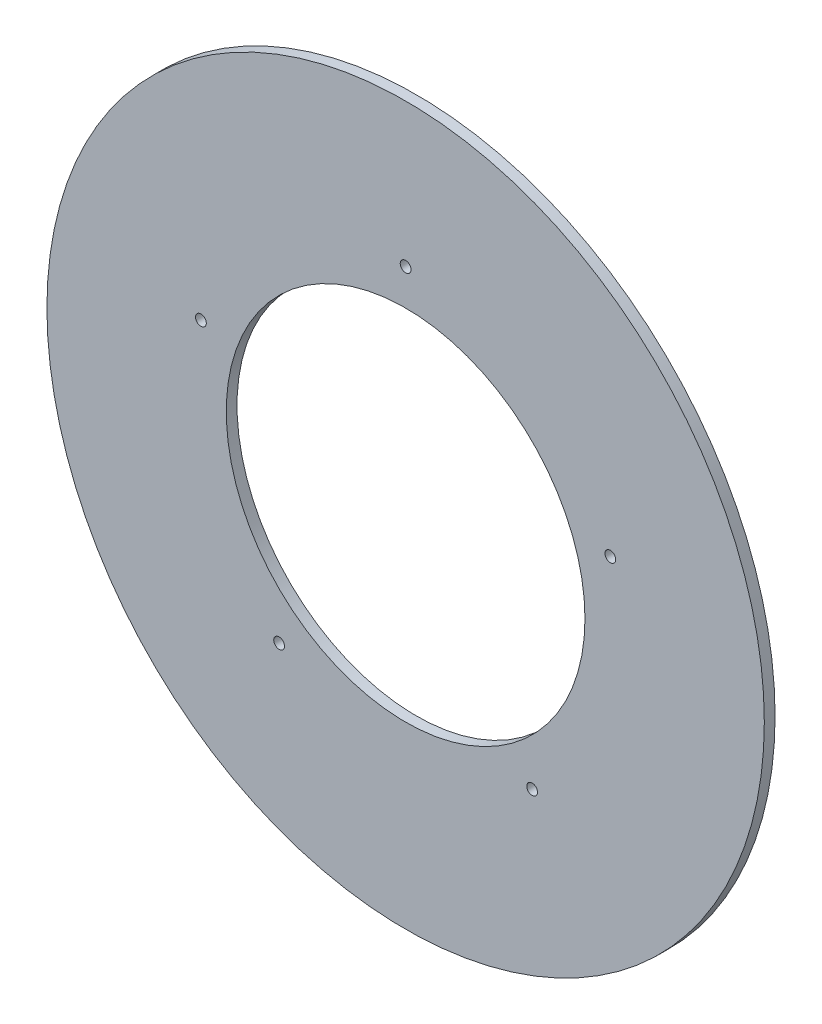
SolidWorks part; units mm, degrees
other "Markup1"
sketch "Sketch5" plane through (-50, -50, 1.5) normal (0, 0, 1) x (1, 0, 0)
ref_plane "Front Plane" through (0, 0, 0) normal (0, 0, 1) x (1, 0, 0)
ref_plane "Top Plane" through (0, 0, 0) normal (0, 1, 0) x (1, 0, 0)
ref_plane "Right Plane" through (0, 0, 0) normal (1, 0, 0) x (0, 0, -1)
sketch "Sketch1" plane through (0, 0, 0) normal (0, 0, 1) x (1, 0, 0)
  circle A0 centre (0, 0) radius 50
  circle A1 centre (0, 0) radius 25
  dimension "D1" = 100
  dimension "D2" = 50
extrude "Boss-Extrude1" add sketch "Sketch1" along normal blind 1.5
sketch "Sketch2" plane through (0, 0, 1.5) normal (0, 0, 1) x (1, 0, 0)
  line L5 (0, 30) -> (-28.5317, 9.2705) construction
  line L6 (-28.5317, 9.2705) -> (-17.6336, -24.2705) construction
  line L7 (-17.6336, -24.2705) -> (17.6336, -24.2705) construction
  line L8 (17.6336, -24.2705) -> (28.5317, 9.2705) construction
  line L9 (28.5317, 9.2705) -> (0, 30) construction
  circle A1 centre (0, 0) radius 50 construction
  circle A7 centre (0, 30) radius 0.75
  circle A17 centre (28.5317, 9.2705) radius 0.75
  circle A18 centre (17.6336, -24.2705) radius 0.75
  circle A19 centre (-17.6336, -24.2705) radius 0.75
  circle A20 centre (-28.5317, 9.2705) radius 0.75
  circle A21 centre (0, 0) radius 24.2705 construction
  point P9 (0, 0)
  point P18 (0, 0)
  dimension "D1" = 1.5
  dimension "D2" = 5
  dimension "D3" = 30
extrude "Cut-Extrude1" cut sketch "Sketch2" against normal through all
